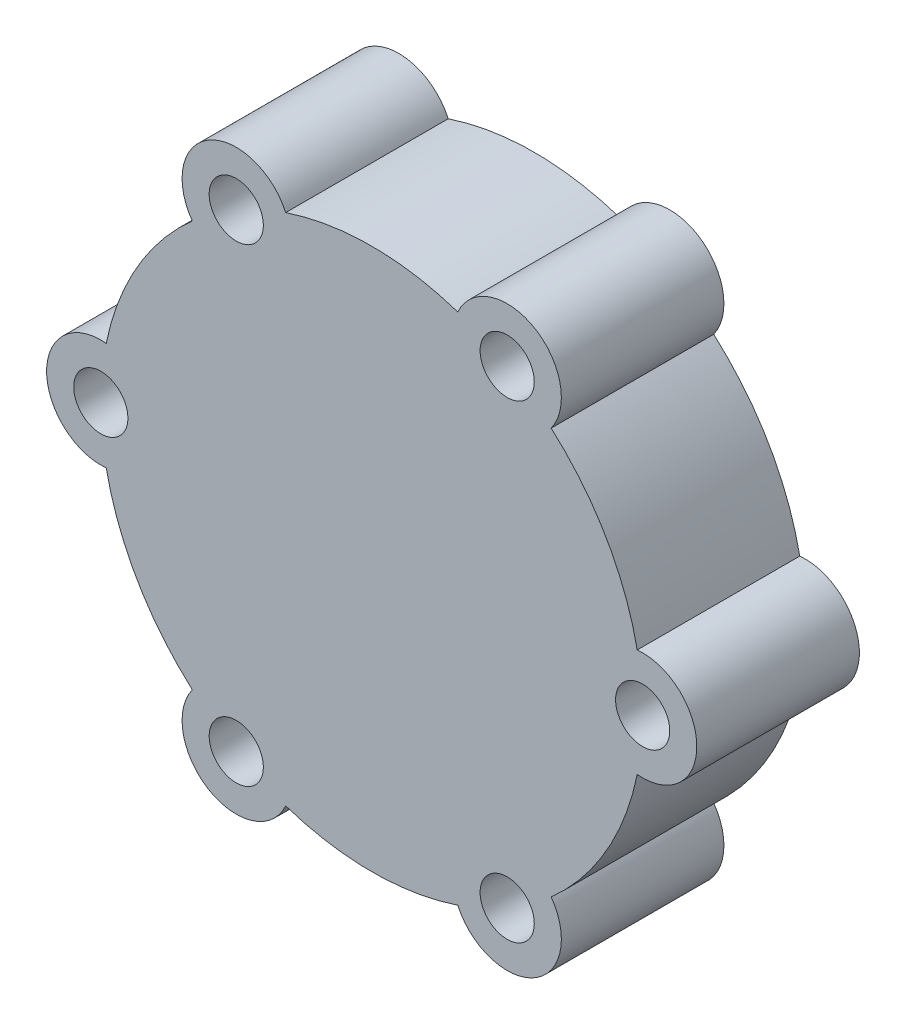
SolidWorks part; units mm, degrees
ref_plane "Front Plane" through (0, 0, 0) normal (0, 0, 1) x (1, 0, 0)
ref_plane "Top Plane" through (0, 0, 0) normal (0, 1, 0) x (1, 0, 0)
ref_plane "Right Plane" through (0, 0, 0) normal (1, 0, 0) x (0, 0, -1)
sketch "Sketch1" plane through (0, 0, 0) normal (0, 0, 1) x (1, 0, 0)
  line L0 (0, 0) -> (40, 0) construction
  line L1 (0, 0) -> (0, 33262.2243) construction
  line L2 (45, 0) -> (33262.2243, 0) construction
  arc A0 (49, 9.9499) -> (33.1168, 37.4603) centre (0, 0) ccw
  arc A1 (49, -9.9499) -> (49, 9.9499) centre (50, 0) ccw
  circle A2 centre (50, 0) radius 5
  arc A3 (15.8832, -47.4102) -> (33.1168, -37.4603) centre (25, -43.3013) ccw
  circle A4 centre (25, -43.3013) radius 5
  arc A5 (-33.1168, -37.4603) -> (-15.8832, -47.4102) centre (-25, -43.3013) ccw
  circle A6 centre (-25, -43.3013) radius 5
  arc A7 (-49, 9.9499) -> (-49, -9.9499) centre (-50, 0) ccw
  circle A8 centre (-50, 0) radius 5
  arc A9 (-15.8832, 47.4102) -> (-33.1168, 37.4603) centre (-25, 43.3013) ccw
  circle A10 centre (-25, 43.3013) radius 5
  arc A11 (33.1168, 37.4603) -> (15.8832, 47.4102) centre (25, 43.3013) ccw
  circle A12 centre (25, 43.3013) radius 5
  arc A14 (15.8832, 47.4102) -> (-15.8832, 47.4102) centre (0, 0) ccw
  arc A17 (-33.1168, 37.4603) -> (-49, 9.9499) centre (0, 0) ccw
  arc A18 (-49, -9.9499) -> (-33.1168, -37.4603) centre (0, 0) ccw
  arc A20 (-15.8832, -47.4102) -> (15.8832, -47.4102) centre (0, 0) ccw
  arc A22 (33.1168, -37.4603) -> (49, -9.9499) centre (0, 0) ccw
  point P36 (0, 0)
  dimension "D1" = 100
  dimension "D2" = 20
  dimension "D3" = 10
  dimension "D4" = 6
extrude "Boss-Extrude1" add sketch "Sketch1" along normal blind 30
